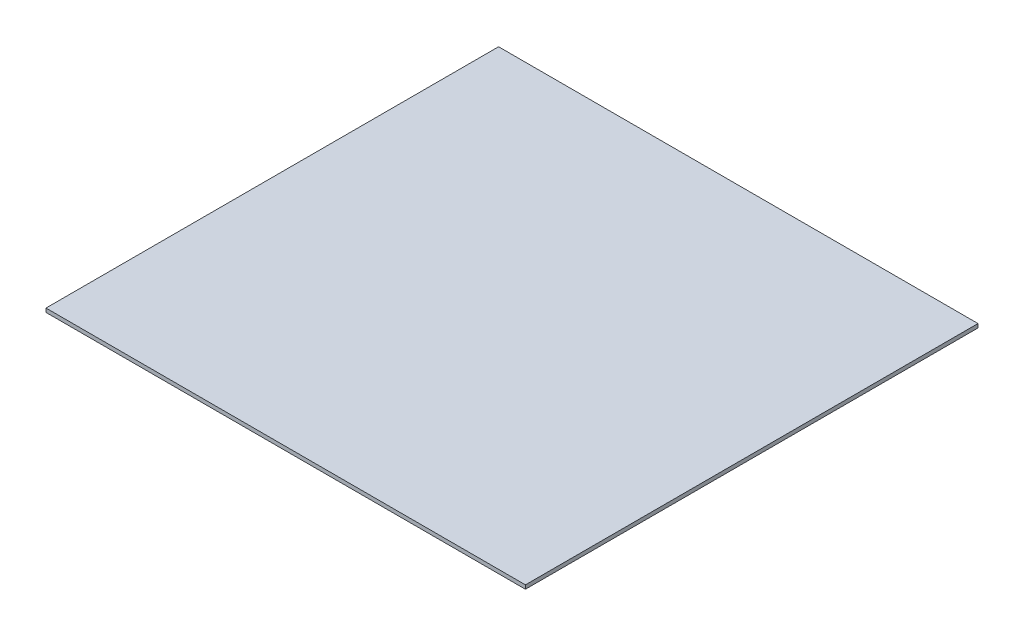
SolidWorks part; units mm, degrees
ref_plane "Front Plane" through (0, 0, 0) normal (0, 0, 1) x (1, 0, 0)
ref_plane "Top Plane" through (0, 0, 0) normal (0, 1, 0) x (1, 0, 0)
ref_plane "Right Plane" through (0, 0, 0) normal (1, 0, 0) x (0, 0, -1)
sketch "Sketch1" plane through (0, 0, 0) normal (0, 1, 0) x (1, 0, 0)
  line L1 (-312.5, 295) -> (312.5, 295)
  line L2 (-312.5, 295) -> (-312.5, -295)
  line L3 (-312.5, -295) -> (312.5, -295)
  line L4 (312.5, 295) -> (312.5, -295)
  line L5 (-312.5, 295) -> (312.5, -295) construction
  line L6 (-312.5, -295) -> (312.5, 295) construction
  point P0 (0, 0)
extrude "Boss-Extrude1" add sketch "Sketch1" along normal blind 5
